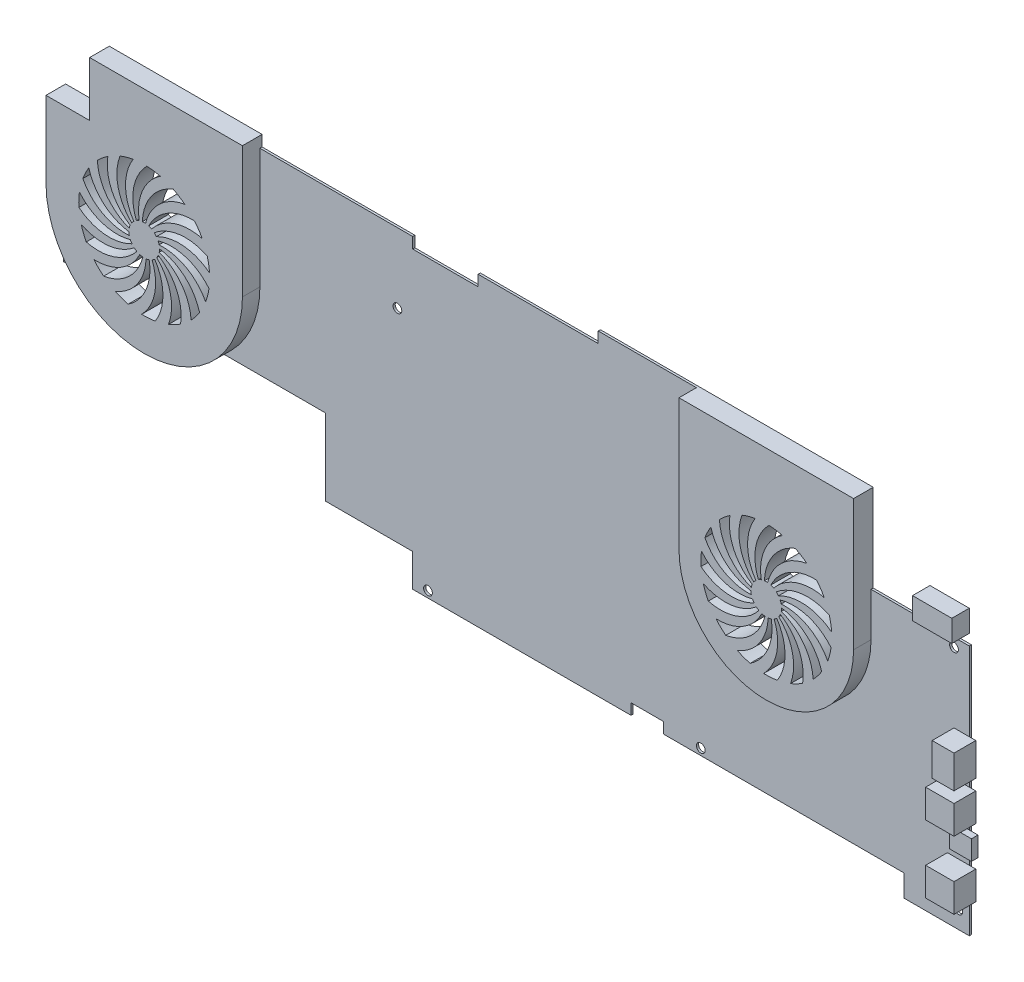
SolidWorks part; units mm, degrees
ref_plane "前基準面" through (0, 0, 0) normal (0, 0, 1) x (1, 0, 0)
ref_plane "上基準面" through (0, 0, 0) normal (0, 1, 0) x (1, 0, 0)
ref_plane "右基準面" through (0, 0, 0) normal (1, 0, 0) x (0, 0, -1)
sketch "草圖2" plane through (0, 0, 0) normal (0, 0, 1) x (1, 0, 0)
  line L0 (0, 0) -> (40, 0)
  line L1 (40, 0) -> (40, -15)
  line L2 (40, -15) -> (140, -15)
  line L3 (140, -15) -> (140, -10)
  line L4 (140, -10) -> (155, -10)
  line L5 (155, -10) -> (155, -15)
  line L6 (155, -15) -> (265, -15)
  line L7 (265, -15) -> (265, -25)
  line L8 (265, -25) -> (295, -25)
  line L9 (295, -25) -> (295, 90)
  line L10 (295, 90) -> (250, 90)
  line L11 (250, 90) -> (250, 130)
  line L12 (250, 130) -> (125, 130)
  line L13 (125, 130) -> (125, 125)
  line L14 (125, 125) -> (70, 125)
  line L15 (70, 125) -> (70, 120)
  line L16 (70, 120) -> (40, 120)
  line L17 (40, 120) -> (40, 125)
  line L18 (40, 125) -> (-30, 125)
  line L19 (-30, 125) -> (-30, 130)
  line L20 (-30, 130) -> (-100, 130)
  line L26 (-100, 130) -> (-100, 105)
  line L27 (-100, 105) -> (-120, 105)
  line L28 (-120, 105) -> (-120, 35)
  line L30 (0, 0) -> (0, 35)
  line L31 (0, 35) -> (-120, 35)
  dimension "D1" = 40
  dimension "D2" = 15
  dimension "D3" = 100
  dimension "D4" = 5
  dimension "D5" = 15
  dimension "D6" = 110
  dimension "D7" = 10
  dimension "D8" = 30
  dimension "D9" = 115
  dimension "D10" = 45
  dimension "D11" = 40
  dimension "D12" = 125
  dimension "D13" = 5
  dimension "D14" = 55
  dimension "D15" = 5
  dimension "D16" = 30
  dimension "D17" = 70
  dimension "D18" = 5
  dimension "D19" = 70
  dimension "D20" = 25
  dimension "D21" = 20
  dimension "D22" = 70
extrude "填料-伸長2" add sketch "草圖2" along normal blind 1 contours L0 L1 L2 L3 L4 L5 L6 L7 L8 L9 L10 L11 L12 L13 L14 L15 L16 L17 L18 L19 L20 L26 L27 L28 L31 L30
sketch "草圖4" plane through (0, 0, 1) normal (0, 0, 1) x (1, 0, 0)
  line L0 (40, 0) -> (40, -15) construction
  line L1 (40, -15) -> (140, -15) construction
  line L2 (155, -15) -> (265, -15) construction
  line L3 (155, -10) -> (155, -15) construction
  line L4 (295, -25) -> (295, 90) construction
  line L5 (265, -25) -> (295, -25) construction
  line L6 (295, 90) -> (250, 90) construction
  line L7 (70, 120) -> (40, 120) construction
  circle A0 centre (47, -12) radius 2
  circle A1 centre (172, -12) radius 2
  circle A2 centre (290, -17) radius 2
  circle A3 centre (288, 86) radius 2
  circle A4 centre (33, 93) radius 2
  dimension "D1" = 4
  dimension "D2" = 7
  dimension "D3" = 3
  dimension "D4" = 3
  dimension "D5" = 17
  dimension "D6" = 5
  dimension "D7" = 8
  dimension "D8" = 7
  dimension "D9" = 4
  dimension "D10" = 27
  dimension "D11" = 14
extrude "除料-伸長1" cut sketch "草圖4" against normal through all
sketch "草圖6" plane through (0, 0, 1) normal (0, 0, 1) x (1, 0, 0)
  line L5 (288, 54) -> (298, 54)
  line L6 (285, 3) -> (285, -10)
  line L7 (285, -10) -> (298, -10)
  line L8 (298, -10) -> (298, 3)
  line L9 (298, 3) -> (285, 3)
  line L10 (288, 54) -> (288, 39)
  line L11 (265, -25) -> (295, -25) construction
  line L12 (295, -25) -> (295, 90) construction
  line L13 (285, 34) -> (285, 21)
  line L14 (285, 21) -> (298, 21)
  line L15 (298, 21) -> (298, 34)
  line L16 (298, 34) -> (285, 34)
  line L17 (288, 39) -> (298, 39)
  line L18 (298, 54) -> (298, 39)
  dimension "D1" = 13
  dimension "D2" = 13
  dimension "D3" = 15
  dimension "D4" = 10
  dimension "D5" = 18
  dimension "D6" = 10
  dimension "D7" = 10
  dimension "D8" = 15
  dimension "D9" = 5
  dimension "D10" = 7
extrude "填料-伸長3" add sketch "草圖6" along normal blind 10
sketch "草圖8" plane through (0, 0, 1) normal (0, 0, 1) x (1, 0, 0)
  line L0 (277, 105) -> (277, 95)
  line L1 (277, 95) -> (295, 95)
  line L2 (295, 95) -> (295, 105)
  line L3 (295, 105) -> (277, 105)
  line L4 (295, 90) -> (250, 90) construction
  line L7 (295, 54) -> (295, 90) construction
  dimension "D1" = 18
  dimension "D2" = 10
  dimension "D3" = 5
extrude "填料-伸長4" add sketch "草圖8" along normal blind 8 separate body
sketch "草圖9" plane through (0, 0, 1) normal (0, 0, 1) x (1, 0, 0)
  line L0 (289, 17) -> (289, 8)
  line L1 (289, 8) -> (299, 8)
  line L2 (299, 8) -> (299, 17)
  line L3 (299, 17) -> (289, 17)
  line L4 (298, 3) -> (285, 3) construction
  line L5 (295, 3) -> (295, 21) construction
  dimension "D1" = 9
  dimension "D2" = 10
  dimension "D3" = 5
  dimension "D4" = 6
extrude "填料-伸長5" add sketch "草圖9" along normal blind 3
sketch "草圖10" plane through (0, 0, 1) normal (0, 0, 1) x (1, 0, 0)
  line L0 (250, 130) -> (250, 70)
  line L1 (170, 70) -> (170, 130)
  line L2 (250, 130) -> (125, 130) construction
  line L3 (170, 130) -> (250, 130)
  line L4 (-30, 130) -> (-30, 70)
  line L5 (-120, 105) -> (-120, 35) construction
  line L6 (-120, 70) -> (-120, 105)
  line L7 (-120, 105) -> (-100, 105)
  line L8 (-100, 105) -> (-100, 130)
  line L9 (-100, 130) -> (-30, 130)
  arc A0 (250, 70) -> (170, 70) centre (210, 70) cw
  arc A1 (-30, 70) -> (-120, 70) centre (-75, 70) cw
  dimension "D2" = 60
  dimension "D1" = 80
extrude "填料-伸長6" add sketch "草圖10" along normal blind 8
sketch "草圖11" plane through (0, 0, 9) normal (0, 0, 1) x (1, 0, 0)
  line L1 (-75, 70) -> (-97.2249, 68.4296) construction
  line L2 (210, 70) -> (187.7751, 68.4296) construction
  line L3 (-30, 130) -> (-100, 130) construction
  line L4 (295, -25) -> (295, 90) construction
  circle A3 centre (-75, 70) radius 7
  circle A4 centre (210, 70) radius 7
  circle A34 centre (-75, 70) radius 30
  arc A35 (-75, 70) -> (-93.5834, 46.4489) centre (-97.2249, 68.4296) cw
  arc A36 (-75, 70) -> (-98.0739, 50.8272) centre (-97.0658, 73.0847) cw
  arc A37 (-75, 70) -> (-101.5559, 56.0435) centre (-95.9422, 77.6051) cw
  arc A38 (-75, 70) -> (-103.8773, 61.8698) centre (-93.9034, 81.793) cw
  arc A39 (-75, 70) -> (-104.9366, 68.0514) centre (-91.0384, 85.4655) cw
  arc A40 (-75, 70) -> (-104.6876, 74.3182) centre (-87.4725, 88.4621) cw
  arc A41 (-75, 70) -> (-103.1411, 80.3962) centre (-83.3614, 90.6519) cw
  arc A42 (-75, 70) -> (-100.3646, 86.0199) centre (-78.8849, 91.939) cw
  arc A43 (-75, 70) -> (-96.4796, 90.9434) centre (-74.2387, 92.2673) cw
  arc A44 (-75, 70) -> (-91.6559, 94.9516) centre (-69.6257, 91.6224) cw
  arc A45 (-75, 70) -> (-86.1042, 97.8693) centre (-65.2475, 90.0325) cw
  arc A46 (-75, 70) -> (-80.0672, 99.569) centre (-61.2957, 87.5671) cw
  arc A47 (-75, 70) -> (-73.8087, 99.9763) centre (-57.9427, 84.334) cw
  arc A48 (-75, 70) -> (-67.6023, 99.0736) centre (-55.3353, 80.4743) cw
  arc A49 (-75, 70) -> (-61.7192, 96.9002) centre (-53.5873, 76.1569) cw
  arc A50 (-75, 70) -> (-56.4166, 93.5511) centre (-52.7751, 71.5704) cw
  arc A51 (-75, 70) -> (-51.9261, 89.1728) centre (-52.9342, 66.9153) cw
  arc A52 (-75, 70) -> (-48.4441, 83.9565) centre (-54.0578, 62.3949) cw
  arc A53 (-75, 70) -> (-46.1227, 78.1302) centre (-56.0966, 58.207) cw
  arc A54 (-75, 70) -> (-45.0634, 71.9486) centre (-58.9616, 54.5345) cw
  arc A55 (-75, 70) -> (-45.3124, 65.6818) centre (-62.5275, 51.5379) cw
  arc A56 (-75, 70) -> (-46.8589, 59.6038) centre (-66.6386, 49.3481) cw
  arc A57 (-75, 70) -> (-49.6354, 53.9801) centre (-71.1151, 48.061) cw
  arc A58 (-75, 70) -> (-53.5204, 49.0566) centre (-75.7613, 47.7327) cw
  arc A59 (-75, 70) -> (-58.3441, 45.0484) centre (-80.3743, 48.3776) cw
  arc A60 (-75, 70) -> (-63.8958, 42.1307) centre (-84.7525, 49.9675) cw
  arc A61 (-75, 70) -> (-69.9328, 40.431) centre (-88.7043, 52.4329) cw
  arc A62 (-75, 70) -> (-76.1913, 40.0237) centre (-92.0573, 55.666) cw
  arc A63 (-75, 70) -> (-82.3977, 40.9264) centre (-94.6647, 59.5257) cw
  arc A64 (-75, 70) -> (-88.2808, 43.0998) centre (-96.4127, 63.8431) cw
  circle A65 centre (210, 70) radius 30
  arc A66 (210, 70) -> (191.4166, 46.4489) centre (187.7751, 68.4296) cw
  arc A67 (210, 70) -> (186.9261, 50.8272) centre (187.9342, 73.0847) cw
  arc A68 (210, 70) -> (183.4441, 56.0435) centre (189.0578, 77.6051) cw
  arc A69 (210, 70) -> (181.1227, 61.8698) centre (191.0966, 81.793) cw
  arc A70 (210, 70) -> (180.0634, 68.0514) centre (193.9616, 85.4655) cw
  arc A71 (210, 70) -> (180.3124, 74.3182) centre (197.5275, 88.4621) cw
  arc A72 (210, 70) -> (181.8589, 80.3962) centre (201.6386, 90.6519) cw
  arc A73 (210, 70) -> (184.6354, 86.0199) centre (206.1151, 91.939) cw
  arc A74 (210, 70) -> (188.5204, 90.9434) centre (210.7613, 92.2673) cw
  arc A75 (210, 70) -> (193.3441, 94.9516) centre (215.3743, 91.6224) cw
  arc A76 (210, 70) -> (198.8958, 97.8693) centre (219.7525, 90.0325) cw
  arc A77 (210, 70) -> (204.9328, 99.569) centre (223.7043, 87.5671) cw
  arc A78 (210, 70) -> (211.1913, 99.9763) centre (227.0573, 84.334) cw
  arc A79 (210, 70) -> (217.3977, 99.0736) centre (229.6647, 80.4743) cw
  arc A80 (210, 70) -> (223.2808, 96.9002) centre (231.4127, 76.1569) cw
  arc A81 (210, 70) -> (228.5834, 93.5511) centre (232.2249, 71.5704) cw
  arc A82 (210, 70) -> (233.0739, 89.1728) centre (232.0658, 66.9153) cw
  arc A83 (210, 70) -> (236.5559, 83.9565) centre (230.9422, 62.3949) cw
  arc A84 (210, 70) -> (238.8773, 78.1302) centre (228.9034, 58.207) cw
  arc A85 (210, 70) -> (239.9366, 71.9486) centre (226.0384, 54.5345) cw
  arc A86 (210, 70) -> (239.6876, 65.6818) centre (222.4725, 51.5379) cw
  arc A87 (210, 70) -> (238.1411, 59.6038) centre (218.3614, 49.3481) cw
  arc A88 (210, 70) -> (235.3646, 53.9801) centre (213.8849, 48.061) cw
  arc A89 (210, 70) -> (231.4796, 49.0566) centre (209.2387, 47.7327) cw
  arc A90 (210, 70) -> (226.6559, 45.0484) centre (204.6257, 48.3776) cw
  arc A91 (210, 70) -> (221.1042, 42.1307) centre (200.2475, 49.9675) cw
  arc A92 (210, 70) -> (215.0672, 40.431) centre (196.2957, 52.4329) cw
  arc A93 (210, 70) -> (208.8087, 40.0237) centre (192.9427, 55.666) cw
  arc A94 (210, 70) -> (202.6023, 40.9264) centre (190.3353, 59.5257) cw
  arc A95 (210, 70) -> (196.7192, 43.0998) centre (188.5873, 63.8431) cw
  point P3 (210, 70)
  point P136 (-75, 70)
  dimension "D2" = 60
  dimension "D3" = 14
  dimension "D4" = 285
  dimension "D5" = 22.2803
  dimension "D6" = 60
  dimension "D7" = 22.2803
  dimension "D1" = 14
  dimension "D8" = 60
  dimension "D9" = 85
extrude "除料-伸長8" cut sketch "草圖11" against normal through all contours A3 A36 A34 A35 | A3 A64 A34 A63 | A3 A62 A34 A61 | A3 A60 A34 A59 | A3 A58 A34 A57 | A3 A56 A34 A55 | A3 A54 A34 A53 | A3 A52 A34 A51 | A3 A50 A34 A49 | A3 A48 A34 A47 | A3 A46 A34 A45 | A3 A44 A34 A43 | A3 A42 A34 A41 | A3 A40 A34 A39 | A3 A38 A34 A37 | A4 A95 A65 A94 | A4 A93 A65 A92 | A4 A91 A65 A90 | A4 A89 A65 A88 | A4 A87 A65 A86 | A4 A85 A65 A84 | A4 A83 A65 A82 | A4 A81 A65 A80 | A4 A79 A65 A78 | A4 A77 A65 A76 | A4 A75 A65 A74 | A4 A73 A65 A72 | A4 A71 A65 A70 | A4 A69 A65 A68 | A4 A67 A65 A66
